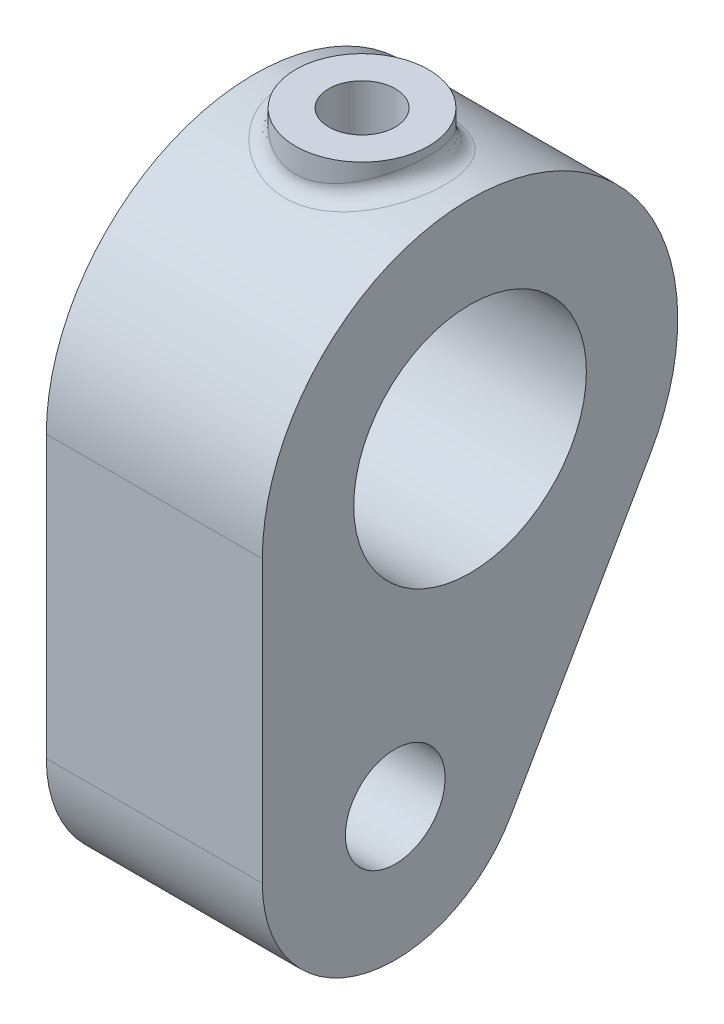
SolidWorks part; units mm, degrees
ref_plane "前基準面" through (0, 0, 0) normal (0, 0, 1) x (1, 0, 0)
ref_plane "上基準面" through (0, 0, 0) normal (0, 1, 0) x (1, 0, 0)
ref_plane "右基準面" through (0, 0, 0) normal (1, 0, 0) x (0, 0, -1)
sketch "草圖1" plane through (0, 0, 0) normal (1, 0, 0) x (0, 0, -1)
  line L0 (-25, -33.8231) -> (-25, 0)
  line L1 (21.6939, -12.4248) -> (4.8841, -41.7749)
  arc A0 (-25, 0) -> (21.6939, -12.4248) centre (0, 0) cw
  arc A1 (4.8841, -41.7749) -> (-25, -33.8231) centre (-9, -33.8231) cw
  circle A2 centre (0, 0) radius 14
  circle A3 centre (-9, -33.8231) radius 6
  dimension "D1" = 25
  dimension "D2" = 16
  dimension "D3" = 12
  dimension "D4" = 28
  dimension "D5" = 35
extrude "伸長1" add sketch "草圖1" along normal mid plane 26
ref_plane "平面1" through (0, 28, 0) normal (0, 1, 0) x (-1, 0, 0)
sketch "草圖2" plane through (0, 28, 0) normal (0, 1, 0) x (-1, 0, 0)
  circle A0 centre (0, 0) radius 8
  dimension "D1" = 16
extrude "伸長2" add sketch "草圖2" against normal up to next
sketch "草圖3" plane through (0, 28, 0) normal (0, 1, 0) x (1, 0, 0)
  circle A0 centre (0, 0) radius 4
  dimension "D1" = 8
extrude "伸長3" cut sketch "草圖3" against normal up to next
fillet "圓角1" radius 2 1 edges at (-1.4021, 23.7269, -7.8762)
